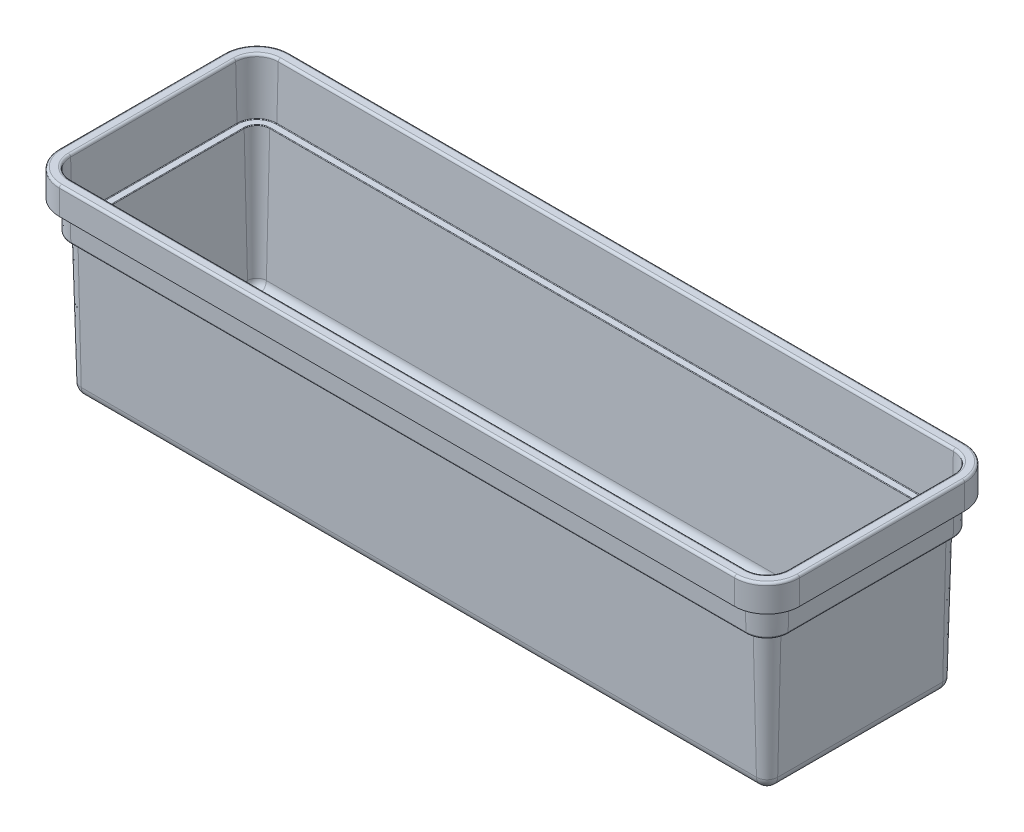
SolidWorks part; units mm, degrees
ref_plane "Front Plane" through (0, 0, 0) normal (0, 0, 1) x (1, 0, 0)
ref_plane "Top Plane" through (0, 0, 0) normal (0, 1, 0) x (1, 0, 0)
ref_plane "Right Plane" through (0, 0, 0) normal (1, 0, 0) x (0, 0, -1)
sketch "Sketch1" plane through (0, 0, 0) normal (1, 0, 0) x (0, 0, -1)
  line L0 (77.5, 7.7942) -> (80.3287, 117.7129)
  line L1 (86.3557, 118.6871) -> (87.5, 163.1515)
  line L2 (89.4993, 165.1) -> (95.025, 165.1)
  line L3 (97.025, 163.1) -> (97.025, 142.3)
  line L4 (69.5026, 0) -> (0, 0) construction
  line L5 (80.8285, 118.2) -> (85.8559, 118.2)
  arc A0 (80.3287, 117.7129) -> (80.8285, 118.2) centre (80.8285, 117.7) cw
  arc A1 (85.8559, 118.2) -> (86.3557, 118.6871) centre (85.8559, 118.7) ccw
  arc A2 (87.5, 163.1515) -> (89.4993, 165.1) centre (89.4993, 163.1) cw
  arc A3 (95.025, 165.1) -> (97.025, 163.1) centre (95.025, 163.1) cw
  arc A4 (77.5, 7.7942) -> (69.5026, 0) centre (69.5026, 8) cw
  dimension "D6" = 8
  dimension "D7" = 0.5
  dimension "D8" = 2
  dimension "D1" = 165.1
  dimension "D2" = 22.8
  dimension "D3" = 46.9
  dimension "D4" = 6
  dimension "D5" = 9.525
  dimension "D9" = 87.5
  dimension "D10" = 77.5
extrude "Extrude-Thin1" add sketch "Sketch1" along normal blind 571.5 thin
sketch "Sketch4" plane through (571.5, 0, 0) normal (1, 0, 0) x (0, 0, -1)
  line L0 (69.5026, -1) -> (69.5026, 169.3186) construction
  line L11 (96.025, 163.1) -> (96.025, 142.3)
  line L12 (96.025, 142.3) -> (97.025, 142.3)
  line L13 (97.025, 142.3) -> (97.025, 163.1)
  line L14 (95.025, 165.1) -> (89.4993, 165.1)
  line L15 (87.5, 163.1515) -> (86.3557, 118.6871)
  line L16 (80.3287, 117.7129) -> (77.5, 7.7942)
  line L17 (69.5026, 0) -> (69.5026, -1)
  line L18 (78.4997, 7.7685) -> (81.3158, 117.2)
  line L19 (87.3554, 118.6614) -> (88.4997, 163.1257)
  line L20 (89.4993, 164.1) -> (95.025, 164.1)
  line L21 (96.025, 163.1) -> (96.025, 142.3)
  line L22 (96.025, 142.3) -> (97.025, 142.3)
  line L23 (97.025, 142.3) -> (97.025, 163.1)
  line L24 (95.025, 165.1) -> (89.4993, 165.1)
  line L25 (87.5, 163.1515) -> (86.3557, 118.6871)
  line L26 (80.3287, 117.7129) -> (77.5, 7.7942)
  line L27 (69.5026, 0) -> (69.5026, -1)
  line L28 (78.4997, 7.7685) -> (81.3158, 117.2)
  line L29 (87.3554, 118.6614) -> (88.4997, 163.1257)
  line L30 (89.4993, 164.1) -> (95.025, 164.1)
  line L33 (85.8559, 118.2) -> (80.8285, 118.2)
  line L34 (85.8559, 118.2) -> (80.8285, 118.2)
  line L35 (81.3158, 117.2) -> (85.8559, 117.2)
  line L36 (81.3158, 117.2) -> (85.8559, 117.2)
  arc A9 (85.8559, 118.2) -> (86.3557, 118.6871) centre (85.8559, 118.7) ccw
  arc A10 (97.025, 163.1) -> (95.025, 165.1) centre (95.025, 163.1) ccw
  arc A11 (89.4993, 165.1) -> (87.5, 163.1515) centre (89.4993, 163.1) ccw
  arc A12 (85.8559, 118.2) -> (86.3557, 118.6871) centre (85.8559, 118.7) ccw
  arc A13 (80.8285, 118.2) -> (80.3287, 117.7129) centre (80.8285, 117.7) ccw
  arc A14 (69.5026, 0) -> (77.5, 7.7942) centre (69.5026, 8) ccw
  arc A15 (69.5026, -1) -> (78.4997, 7.7685) centre (69.5026, 8) ccw
  arc A16 (85.8559, 117.2) -> (87.3554, 118.6614) centre (85.8559, 118.7) ccw
  arc A17 (85.8559, 117.2) -> (87.3554, 118.6614) centre (85.8559, 118.7) ccw
  arc A18 (89.4993, 164.1) -> (88.4997, 163.1257) centre (89.4993, 163.1) ccw
  arc A19 (96.025, 163.1) -> (95.025, 164.1) centre (95.025, 163.1) ccw
  arc A20 (97.025, 163.1) -> (95.025, 165.1) centre (95.025, 163.1) ccw
  arc A21 (89.4993, 165.1) -> (87.5, 163.1515) centre (89.4993, 163.1) ccw
  arc A23 (80.8285, 118.2) -> (80.3287, 117.7129) centre (80.8285, 117.7) ccw
  arc A24 (69.5026, 0) -> (77.5, 7.7942) centre (69.5026, 8) ccw
  arc A25 (69.5026, -1) -> (78.4997, 7.7685) centre (69.5026, 8) ccw
  arc A28 (89.4993, 164.1) -> (88.4997, 163.1257) centre (89.4993, 163.1) ccw
  arc A29 (96.025, 163.1) -> (95.025, 164.1) centre (95.025, 163.1) ccw
  dimension "D1" = 0
revolve "Revolve1" add sketch "Sketch4" angle 90 about L0
sketch "Sketch5" plane through (0, 0, -69.5026) normal (0, 0, 1) x (1, 0, 0)
  line L12 (0, 0) -> (0, -1)
  line L13 (0, -1) -> (571.5, -1)
  line L14 (580.497, 7.7685) -> (583.3132, 117.2)
  line L15 (589.3528, 118.6614) -> (590.497, 163.1257)
  line L16 (591.4967, 164.1) -> (597.0224, 164.1)
  line L17 (598.0224, 163.1) -> (598.0224, 142.3)
  line L18 (598.0224, 142.3) -> (599.0224, 142.3)
  line L19 (599.0224, 142.3) -> (599.0224, 163.1)
  line L20 (597.0224, 165.1) -> (591.4967, 165.1)
  line L21 (589.4974, 163.1515) -> (588.3531, 118.6871)
  line L22 (582.326, 117.7129) -> (579.4974, 7.7942)
  line L23 (571.5, 0) -> (0, 0)
  line L24 (0, 0) -> (0, -1)
  line L25 (0, -1) -> (571.5, -1)
  line L26 (580.497, 7.7685) -> (583.3132, 117.2)
  line L27 (589.3528, 118.6614) -> (590.497, 163.1257)
  line L28 (591.4967, 164.1) -> (597.0224, 164.1)
  line L29 (598.0224, 163.1) -> (598.0224, 142.3)
  line L30 (598.0224, 142.3) -> (599.0224, 142.3)
  line L31 (599.0224, 142.3) -> (599.0224, 163.1)
  line L32 (597.0224, 165.1) -> (591.4967, 165.1)
  line L33 (589.4974, 163.1515) -> (588.3531, 118.6871)
  line L34 (582.326, 117.7129) -> (579.4974, 7.7942)
  line L35 (571.5, 0) -> (0, 0)
  line L38 (583.3132, 117.2) -> (587.8533, 117.2)
  line L39 (583.3132, 117.2) -> (587.8533, 117.2)
  line L40 (587.8533, 118.2) -> (582.8259, 118.2)
  line L41 (587.8533, 118.2) -> (582.8259, 118.2)
  arc A9 (587.8533, 117.2) -> (589.3528, 118.6614) centre (587.8533, 118.7) ccw
  arc A10 (571.5, -1) -> (580.497, 7.7685) centre (571.5, 8) ccw
  arc A11 (587.8533, 117.2) -> (589.3528, 118.6614) centre (587.8533, 118.7) ccw
  arc A12 (587.8533, 118.2) -> (588.3531, 118.6871) centre (587.8533, 118.7) ccw
  arc A13 (591.4967, 164.1) -> (590.497, 163.1257) centre (591.4967, 163.1) ccw
  arc A14 (598.0224, 163.1) -> (597.0224, 164.1) centre (597.0224, 163.1) ccw
  arc A15 (599.0224, 163.1) -> (597.0224, 165.1) centre (597.0224, 163.1) ccw
  arc A16 (591.4967, 165.1) -> (589.4974, 163.1515) centre (591.4967, 163.1) ccw
  arc A17 (587.8533, 118.2) -> (588.3531, 118.6871) centre (587.8533, 118.7) ccw
  arc A18 (582.8259, 118.2) -> (582.326, 117.7129) centre (582.8259, 117.7) ccw
  arc A19 (571.5, 0) -> (579.4974, 7.7942) centre (571.5, 8) ccw
  arc A20 (571.5, -1) -> (580.497, 7.7685) centre (571.5, 8) ccw
  arc A23 (591.4967, 164.1) -> (590.497, 163.1257) centre (591.4967, 163.1) ccw
  arc A24 (598.0224, 163.1) -> (597.0224, 164.1) centre (597.0224, 163.1) ccw
  arc A25 (599.0224, 163.1) -> (597.0224, 165.1) centre (597.0224, 163.1) ccw
  arc A26 (591.4967, 165.1) -> (589.4974, 163.1515) centre (591.4967, 163.1) ccw
  arc A28 (582.8259, 118.2) -> (582.326, 117.7129) centre (582.8259, 117.7) ccw
  arc A29 (571.5, 0) -> (579.4974, 7.7942) centre (571.5, 8) ccw
  dimension "D1" = 0
extrude "Boss-Extrude1" add sketch "Sketch5" along normal blind 139.7
ref_plane "Plane1" through (285.75, 0, 0) normal (1, 0, 0) x (0, 0, -1)
mirror "Mirror1" about plane through (285.75, 0, 0) normal (1, 0, 0) of "Boss-Extrude1", "Revolve1"
ref_plane "Plane2" through (0, 0, 0.3474) normal (0, 0, 1) x (1, 0, 0)
mirror "Mirror2" about plane through (0, 0, 0.3474) normal (0, 0, 1) of "Mirror1", "Revolve1", "Extrude-Thin1"
